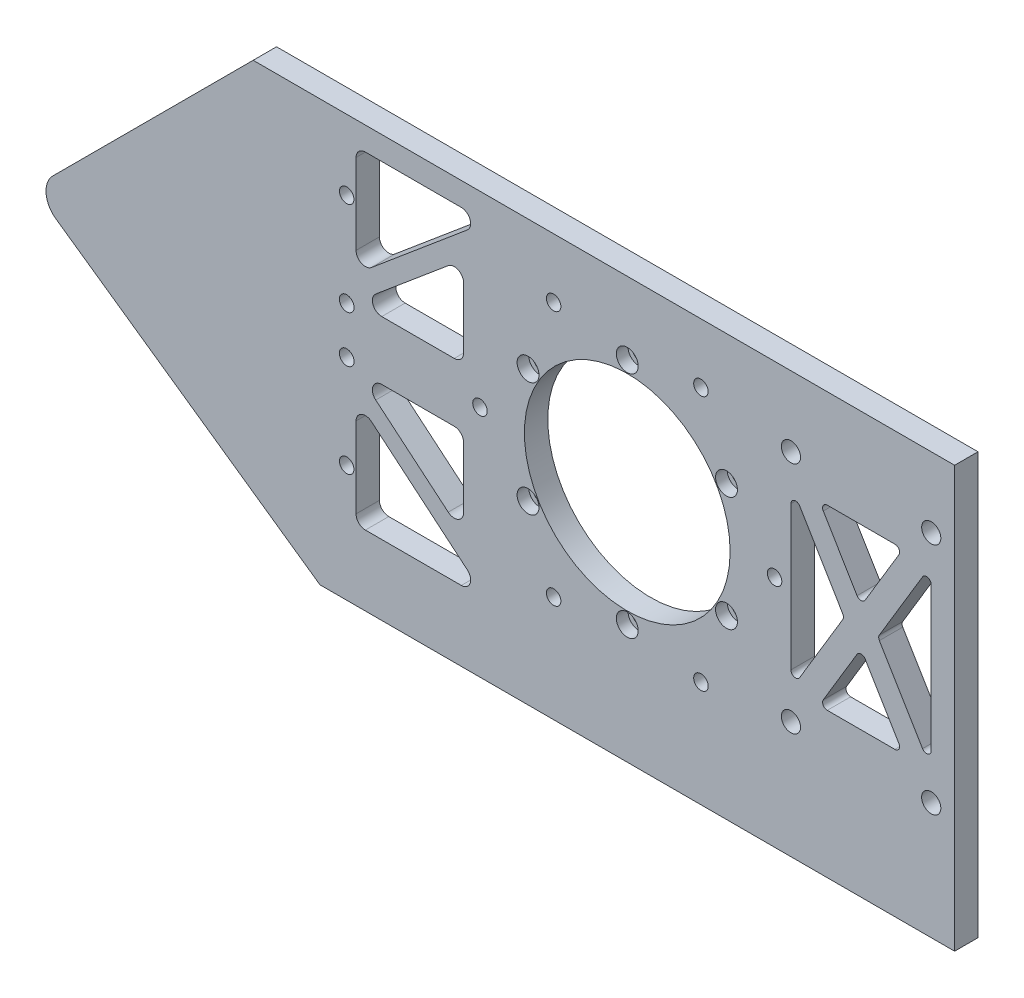
SolidWorks part; units mm, degrees
ref_plane "前视基准面" through (0, 0, 0) normal (0, 0, 1) x (1, 0, 0)
ref_plane "上视基准面" through (0, 0, 0) normal (0, 1, 0) x (1, 0, 0)
ref_plane "右视基准面" through (0, 0, 0) normal (1, 0, 0) x (0, 0, -1)
sketch "草图1" plane through (0, 0, 0) normal (0, 0, 1) x (1, 0, 0)
  line L1 (-80, 40) -> (70, 40)
  line L2 (-80, 40) -> (-80, -40)
  line L3 (-80, -40) -> (70, -40)
  line L4 (70, 40) -> (70, -40)
  circle A0 centre (0, 0) radius 24.5 construction
  circle A1 centre (0, -24.5) radius 1.3
  circle A2 centre (-21.2176, -12.25) radius 1.3
  circle A3 centre (-21.2176, 12.25) radius 1.3
  circle A4 centre (0, 0) radius 22
  circle A5 centre (0, 24.5) radius 1.3
  circle A6 centre (21.2176, 12.25) radius 1.3
  circle A7 centre (21.2176, -12.25) radius 1.3
  point P11 (0, 0)
  point P15 (70, 0)
  dimension "D1" = 49
  dimension "D2" = 2.6
  dimension "D4" = 44
  dimension "D5" = 80
  dimension "D6" = 70
  dimension "D7" = 80
  dimension "D3" = 6
extrude "凸台-拉伸1" add sketch "草图1" along normal blind 5
sketch "草图2" plane through (0, 0, 5) normal (0, 0, 1) x (1, 0, 0)
  circle A0 centre (-21.2176, 12.25) radius 2.34
  circle A1 centre (0, 24.5) radius 2.34
  circle A2 centre (21.2176, 12.25) radius 2.34
  circle A3 centre (21.2176, -12.25) radius 2.34
  circle A4 centre (0, -24.5) radius 2.34
  circle A5 centre (-21.2176, -12.25) radius 2.34
  point P15 (0, 0)
  dimension "D1" = 4.68
  dimension "D2" = 6
extrude "切除-拉伸1" cut sketch "草图2" against normal blind 2.5
sketch "草图3" plane through (0, 0, 5) normal (0, 0, 1) x (1, 0, 0)
  line L0 (0, 0) -> (-60, 0) construction
  line L1 (-60, 0) -> (-60, -25) construction
  line L3 (-60, 0) -> (-60, 24.3133)
  circle A4 centre (-60, -25) radius 1.55
  circle A5 centre (-60, -5) radius 1.5828
  circle A6 centre (-60, 25) radius 1.55
  circle A7 centre (-60, 5) radius 1.5828
  point P6 (-60, 0)
  dimension "D3" = 3.1
  dimension "D4" = 20
  dimension "D1" = 60
  dimension "D2" = 25
extrude "切除-拉伸3" cut sketch "草图3" against normal blind 12.5
sketch "草图4" plane through (0, 0, 5) normal (0, 0, 1) x (1, 0, 0)
  line L0 (-58, 35) -> (-30, 35)
  line L1 (-30, 35) -> (-58, 11.5052)
  line L2 (-58, 11.5052) -> (-58, 35)
  line L3 (-35, 25.5829) -> (-58, 6.2836)
  line L4 (-58, 6.2836) -> (-35, 6.2836)
  line L5 (-35, 6.2836) -> (-35, 25.5829)
  line L8 (70, 40) -> (-80, 40) construction
  line L9 (-80, 40) -> (-80, -40) construction
  dimension "D1" = 5
  dimension "D2" = 22
  dimension "D3" = 140
  dimension "D4" = 45
  dimension "D6" = 4
extrude "切除-拉伸5" cut sketch "草图4" against normal blind 8 contours L2 L0 L1 | L5 L3 L4
fillet "圆角3" radius 2 6 edges at (-35, 6.2836, 2.5) (-58, 6.2836, 2.5) (-35, 25.5829, 2.5) (-30, 35, 2.5) (-58, 11.5052, 2.5) (-58, 35, 2.5)
mirror "镜向2" about plane through (0, 0, 0) normal (0, 1, 0) of "圆角3", "切除-拉伸5"
sketch "草图10" plane through (0, 0, 5) normal (0, 0, 1) x (1, 0, 0)
  line L0 (-80, -40) -> (-127.0531, -7.0531)
  line L1 (-127.0531, -7.0531) -> (-80, 40)
  line L2 (-80, -40) -> (70, -40) construction
  line L3 (-80, 40) -> (-80, -40) construction
  line L4 (-80, 40) -> (-80, -40)
  dimension "D1" = 145
  dimension "D2" = 45
extrude "凸台-拉伸4" add sketch "草图10" against normal up to surface (5 mm away) contours L4 L0 L1 up to face at (-49.3474, 27.3903, 0)
fillet "圆角5" radius 5 1 edges at (-127.0531, -7.0531, 2.5)
sketch "草图11" plane through (0, 0, 5) normal (0, 0, 1) x (1, 0, 0)
  line L0 (0, 0) -> (0, 34) construction
  line L1 (0, 0) -> (-15.75, 27.2798)
  circle A0 centre (0, 0) radius 29 construction
  circle A1 centre (0, 0) radius 34 construction
  circle A2 centre (0, 0) radius 31.5 construction
  circle A3 centre (-15.75, 27.2798) radius 1.55
  circle A4 centre (15.75, 27.2798) radius 1.55
  circle A5 centre (31.5, 0) radius 1.55
  circle A6 centre (15.75, -27.2798) radius 1.55
  circle A7 centre (-15.75, -27.2798) radius 1.55
  circle A8 centre (-31.5, 0) radius 1.55
  point P20 (0, 0)
  dimension "D1" = 58
  dimension "D2" = 68
  dimension "D3" = 63
  dimension "D5" = 3.1
  dimension "D4" = 30
  dimension "D6" = 6
extrude "切除-拉伸7" cut sketch "草图11" against normal blind 25 contours A3 | A4 | A5 | A6 | A7 | A8
sketch "草图12" plane through (0, 0, 5) normal (0, 0, 1) x (1, 0, 0)
  line L0 (0, 0) -> (50, 0) construction
  line L6 (35, -25) -> (65, -25) construction
  line L7 (35, -25) -> (35, 25) construction
  line L8 (35, 25) -> (65, 25) construction
  line L9 (65, -25) -> (65, 25) construction
  line L10 (35, -25) -> (65, 25) construction
  line L11 (35, 25) -> (65, -25) construction
  circle A0 centre (0, 0) radius 28 construction
  circle A1 centre (35, 25) radius 2.05
  circle A2 centre (65, 25) radius 2.05
  circle A3 centre (65, -25) radius 2.05
  circle A4 centre (35, -25) radius 2.05
  dimension "D3" = 56
  dimension "D5" = 4.1
  dimension "D6" = 4.1
  dimension "D1" = 30
  dimension "D2" = 50
  dimension "D4" = 50
extrude "切除-拉伸8" cut sketch "草图12" against normal blind 10
sketch "草图13" plane through (0, 0, 5) normal (0, 0, 1) x (1, 0, 0)
  line L0 (35, 25) -> (65, -25) construction
  line L6 (35, 25) -> (65, -25) construction
  line L10 (35, 19) -> (35, -19)
  line L11 (35, -19) -> (46.4, 0)
  line L12 (46.4, 0) -> (35, 19)
  line L13 (35, -25) -> (65, 25) construction
  line L14 (50, 0) -> (50, -49.4768) construction
  line L15 (65, -19) -> (53.6, 0)
  line L16 (65, 19) -> (65, -19)
  line L17 (53.6, 0) -> (65, 19)
  line L18 (41, 19) -> (50, 4)
  line L19 (50, 4) -> (59, 19)
  line L20 (59, 19) -> (41, 19)
  line L21 (35, 19) -> (65, 19) construction
  line L22 (50, 0) -> (90.4004, 0) construction
  line L23 (50, -4) -> (59, -19)
  line L24 (41, -19) -> (50, -4)
  line L25 (59, -19) -> (41, -19)
  circle A0 centre (35, -25) radius 2.05 construction
  circle A1 centre (65, 25) radius 2.05 construction
  point P4 (50, 0)
  dimension "D1" = 6
  dimension "D2" = 6
  dimension "D3" = 6
  dimension "D4" = 6
  dimension "D5" = 0
extrude "切除-拉伸9" cut sketch "草图13" against normal blind 10
fillet "圆角6" radius 1 12 edges at (35, -19, 2.5) (46.4, 0, 2.5) (35, 19, 2.5) (41, -19, 2.5) (50, -4, 2.5) (59, -19, 2.5) (65, -19, 2.5) (65, 19, 2.5) (53.6, 0, 2.5) (50, 4, 2.5) (59, 19, 2.5) (41, 19, 2.5)
sketch "草图14" plane through (0, 0, 5) normal (0, 0, 1) x (1, 0, 0)
  line L0 (-80, -40) -> (-65.7185, -50)
  line L1 (-65.7185, -50) -> (70, -50)
  line L2 (70, -50) -> (70, -40)
  line L3 (-80, -40) -> (-122.1719, -10.4709) construction
  line L4 (70, -40) -> (70, 40) construction
  line L5 (-80, -40) -> (70, -40) construction
  line L6 (-80, -40) -> (70, -40)
  dimension "D1" = 180
  dimension "D2" = 180
  dimension "D3" = 10
extrude "凸台-拉伸5" add sketch "草图14" against normal up to surface (5 mm away) contours L6 L0 L1 L2 up to face at (50, 13.974, 0)
